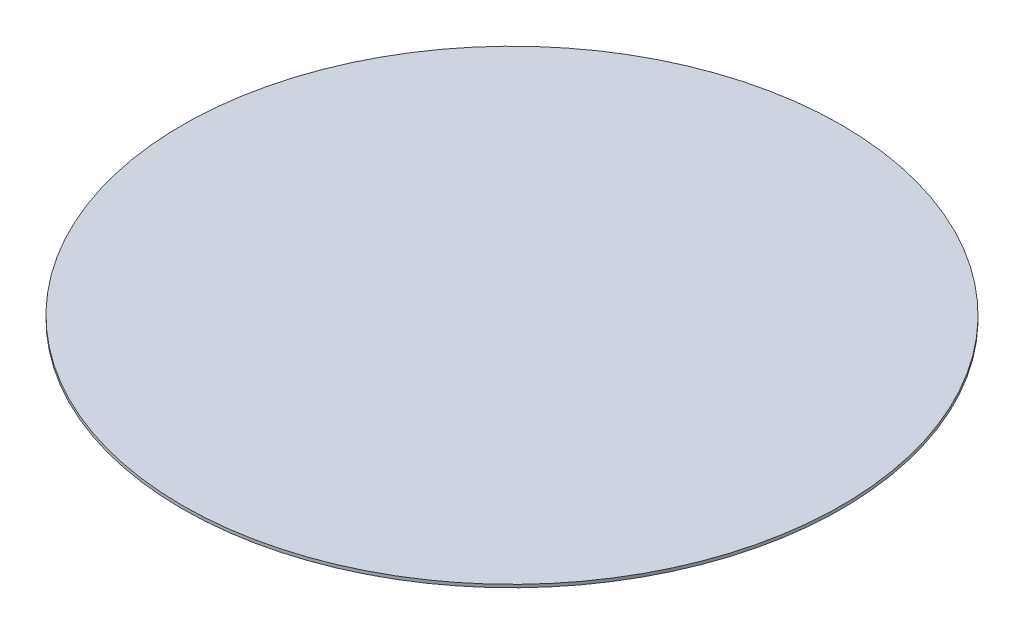
SolidWorks part; units mm, degrees
material "Hexcel AS4C (3000 Filaments)"
ref_plane "Front Plane" through (0, 0, 0) normal (0, 0, 1) x (1, 0, 0)
ref_plane "Top Plane" through (0, 0, 0) normal (0, 1, 0) x (1, 0, 0)
ref_plane "Right Plane" through (0, 0, 0) normal (1, 0, 0) x (0, 0, -1)
sketch "Sketch1" plane through (0, 0, 0) normal (0, 1, 0) x (1, 0, 0)
  circle A0 centre (0, 0) radius 27.5
  dimension "D1" = 55
extrude "Boss-Extrude1" add sketch "Sketch1" along normal blind 0.25 contours A0
